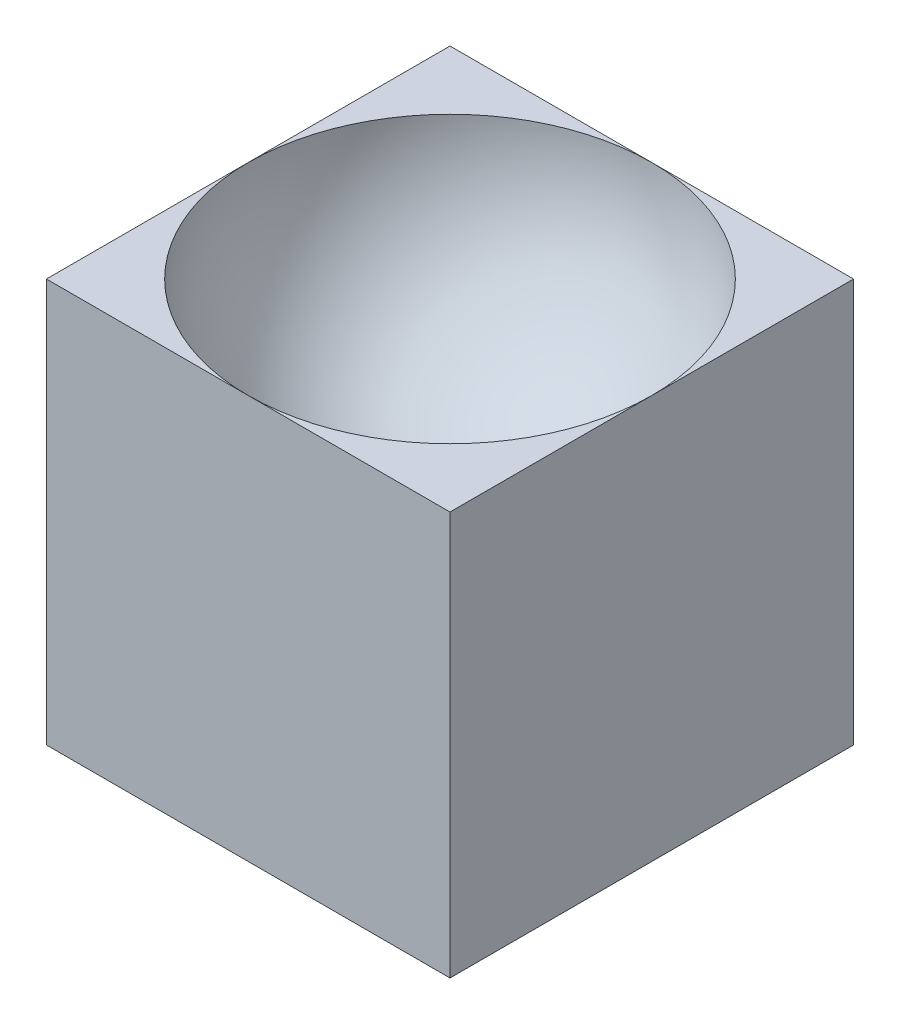
SolidWorks part; units mm, degrees
ref_plane "Front Plane" through (0, 0, 0) normal (0, 0, 1) x (1, 0, 0)
ref_plane "Top Plane" through (0, 0, 0) normal (0, 1, 0) x (1, 0, 0)
ref_plane "Right Plane" through (0, 0, 0) normal (1, 0, 0) x (0, 0, -1)
sketch "Sketch1" plane through (0, 0, 0) normal (0, 1, 0) x (1, 0, 0)
  line L1 (-1, 1) -> (1, 1)
  line L2 (-1, 1) -> (-1, -1)
  line L3 (-1, -1) -> (1, -1)
  line L4 (1, 1) -> (1, -1)
  line L5 (-1, 1) -> (1, -1) construction
  line L6 (-1, -1) -> (1, 1) construction
  point P0 (0, 0)
  dimension "D1" = 2
  dimension "D2" = 2
extrude "Boss-Extrude1" add sketch "Sketch1" along normal blind 2
sketch "Sketch2" plane through (0, 2, 0) normal (0, 1, 0) x (1, 0, 0)
  line L0 (1, 1) -> (-1, 1) construction
  line L1 (-1, -1) -> (1, -1) construction
  line L2 (0, 1) -> (0, -1.0471)
  arc A0 (0, 1) -> (0, -1) centre (0, 0) ccw
revolve "Cut-Revolve1" cut sketch "Sketch2" angle 360 about L2
